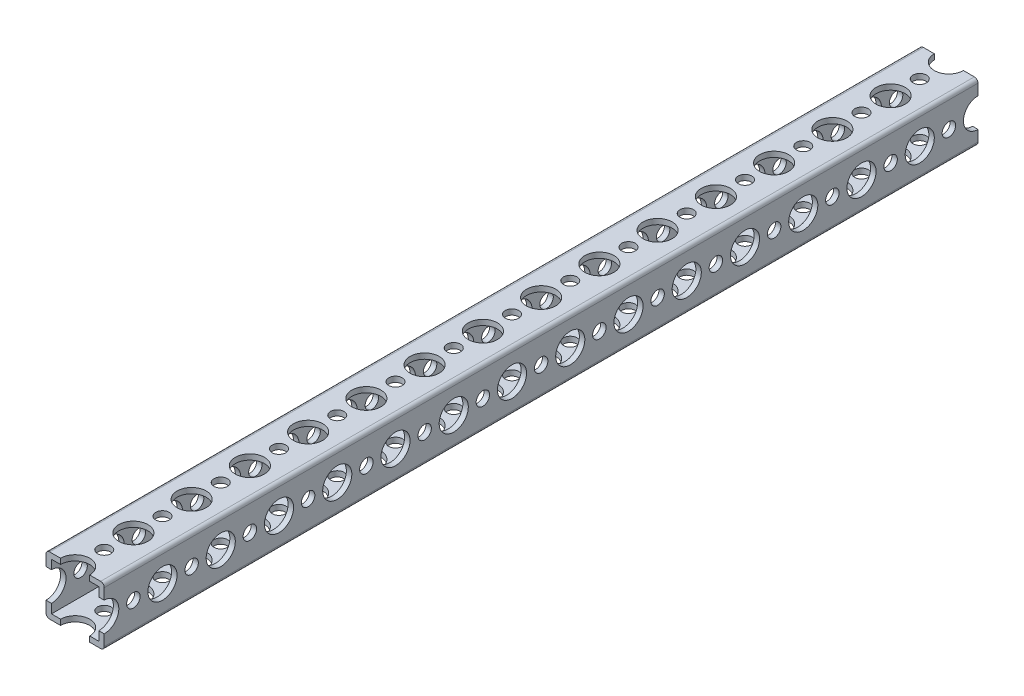
SolidWorks part; units mm, degrees
ref_plane "Front Plane" through (0, 0, 0) normal (0, 0, 1) x (1, 0, 0)
ref_plane "Top Plane" through (0, 0, 0) normal (0, 1, 0) x (1, 0, 0)
ref_plane "Right Plane" through (0, 0, 0) normal (1, 0, 0) x (0, 0, -1)
sketch "Sketch1" plane through (0, 0, 0) normal (0, 0, 1) x (1, 0, 0)
  line L1 (0, 0) -> (16, 0)
  line L2 (0, 0) -> (0, 16)
  line L3 (0, 16) -> (16, 16)
  line L4 (16, 0) -> (16, 16)
  dimension "D1" = 16
  dimension "D2" = 16
extrude "Extrude1" add sketch "Sketch1" against normal blind 240
sketch "Sketch2" plane through (0, 0, 0) normal (0, 0, 1) x (1, 0, 0)
  line L0 (-1.7793, 8) -> (18.8812, 8) construction
  line L1 (8, 16.9255) -> (8, -0.6999) construction
  line L3 (1.5, 14.5) -> (14.5, 14.5)
  line L4 (1.5, 14.5) -> (1.5, 1.5)
  line L5 (1.5, 1.5) -> (14.5, 1.5)
  line L6 (14.5, 14.5) -> (14.5, 1.5)
  line L7 (1.5, 14.5) -> (14.5, 1.5) construction
  line L8 (1.5, 1.5) -> (14.5, 14.5) construction
  point P4 (8, 8)
  dimension "D1" = 13
  dimension "D2" = 13
extrude "Extrude2" cut sketch "Sketch2" against normal through all
sketch "Sketch3" plane through (0, 16, 0) normal (0, 1, 0) x (1, 0, 0)
  line L0 (-10.6019, 48) -> (25.4979, 48) construction
  line L1 (8, -3.3001) -> (8, 305.034) construction
  line L2 (-10.6019, 80) -> (44.8988, 80) construction
  line L4 (16, 0) -> (0, 0) construction
  line L5 (-19.3069, 144) -> (85.0309, 144) construction
  circle A0 centre (8, 64) radius 4
  circle A1 centre (8, 32) radius 4
  circle A3 centre (8, 0) radius 4
  circle A4 centre (8, 96) radius 4
  circle A5 centre (8, 128) radius 4
  circle A6 centre (8, 160) radius 4
  circle A7 centre (8, 192) radius 4
  circle A8 centre (8, 224) radius 4
  circle A9 centre (8, 256) radius 4
  circle B0 centre (8, 48) radius 4
  circle B1 centre (8, 56) radius 1.85
  circle B2 centre (8, 40) radius 1.85
  circle B3 centre (8, 80) radius 4
  circle B4 centre (8, 88) radius 1.85
  circle B5 centre (8, 72) radius 1.85
  circle B6 centre (8, 16) radius 4
  circle B7 centre (8, 24) radius 1.85
  circle B8 centre (8, 8) radius 1.85
  circle B9 centre (8, 112) radius 4
  circle B10 centre (8, 120) radius 1.85
  circle B11 centre (8, 104) radius 1.85
  circle B12 centre (8, 144) radius 4
  circle B13 centre (8, 152) radius 1.85
  circle B14 centre (8, 136) radius 1.85
  circle B15 centre (8, 176) radius 4
  circle B16 centre (8, 184) radius 1.85
  circle B17 centre (8, 168) radius 1.85
  circle B18 centre (8, 208) radius 4
  circle B19 centre (8, 216) radius 1.85
  circle B20 centre (8, 200) radius 1.85
  circle B21 centre (8, 240) radius 4
  circle B22 centre (8, 248) radius 1.85
  circle B23 centre (8, 232) radius 1.85
  dimension "D1" = 24
  dimension "D2" = 16
  dimension "D4" = 16
  dimension "D5" = 32
  dimension "D7" = 16
  dimension "D13" = 48
  dimension "D3" = 24
  dimension "D6" = 64
  dimension "D8" = 48
  dimension "D9" = 32
  dimension "D10" = 64
  dimension "D11" = 96
  dimension "D14" = 16
  dimension "D15" = 80
  dimension "D16" = 112
sketch_block_instance "Block2-1"
sketch_block "Block2"
sketch_block_instance "Block2-4"
sketch_block_instance "Block2-6"
sketch_block_instance "Block2-11"
sketch_block_instance "Block2-12"
sketch_block_instance "Block2-17"
sketch_block_instance "Block2-18"
sketch_block_instance "Block2-19"
extrude "Extrude3" cut sketch "Sketch3" against normal through all
sketch "Sketch4" plane through (16, 0, 0) normal (1, 0, 0) x (0, 0, -1)
  line L0 (-4.9809, 8) -> (308.0277, 8) construction
  line L1 (48, 20.3919) -> (48, -4.2435) construction
  line L2 (0, 0) -> (0, 16) construction
  line L4 (80, -7.5844) -> (80, 23.8371) construction
  line L5 (144, 22.3836) -> (144, -28.3788) construction
  circle A0 centre (32, 8) radius 4
  circle A1 centre (64, 8) radius 4
  circle A2 centre (0, 8) radius 4
  circle A4 centre (96, 8) radius 4
  circle A5 centre (128, 8) radius 4
  circle A6 centre (160, 8) radius 4
  circle A7 centre (192, 8) radius 4
  circle A8 centre (224, 8) radius 4
  circle A9 centre (256, 8) radius 4
  circle B0 centre (48, 8.0742) radius 4
  circle B1 centre (40, 8.0742) radius 1.85
  circle B2 centre (56, 8.0742) radius 1.85
  circle B3 centre (80, 8) radius 4
  circle B4 centre (72, 8) radius 1.85
  circle B5 centre (88, 8) radius 1.85
  circle B6 centre (16, 8) radius 4
  circle B7 centre (8, 8) radius 1.85
  circle B8 centre (24, 8) radius 1.85
  circle B9 centre (112, 8) radius 4
  circle B10 centre (104, 8) radius 1.85
  circle B11 centre (120, 8) radius 1.85
  circle B12 centre (144, 8) radius 4
  circle B13 centre (136, 8) radius 1.85
  circle B14 centre (152, 8) radius 1.85
  circle B15 centre (176, 8) radius 4
  circle B16 centre (168, 8) radius 1.85
  circle B17 centre (184, 8) radius 1.85
  circle B18 centre (208, 8) radius 4
  circle B19 centre (200, 8) radius 1.85
  circle B20 centre (216, 8) radius 1.85
  circle B21 centre (240, 8) radius 4
  circle B22 centre (232, 8) radius 1.85
  circle B23 centre (248, 8) radius 1.85
  dimension "D3" = 16
  dimension "D5" = 32
  dimension "D7" = 16
  dimension "D13" = 16
  dimension "D1" = 24
  dimension "D2" = 24
  dimension "D4" = 16
  dimension "D6" = 64
  dimension "D8" = 48
  dimension "D9" = 32
  dimension "D10" = 64
  dimension "D11" = 96
  dimension "D14" = 48
  dimension "D15" = 80
  dimension "D16" = 112
sketch_block_instance "Block2-8"
sketch_block_instance "Block2-9"
sketch_block_instance "Block2-10"
sketch_block_instance "Block2-14"
sketch_block_instance "Block2-15"
sketch_block_instance "Block2-22"
sketch_block_instance "Block2-23"
sketch_block_instance "Block2-24"
extrude "Extrude4" cut sketch "Sketch4" against normal through all
fillet "Fillet1" radius 1 4 edges at (0, 0, -120) (16, 0, -120) (0, 16, -120) (16, 16, -120)
